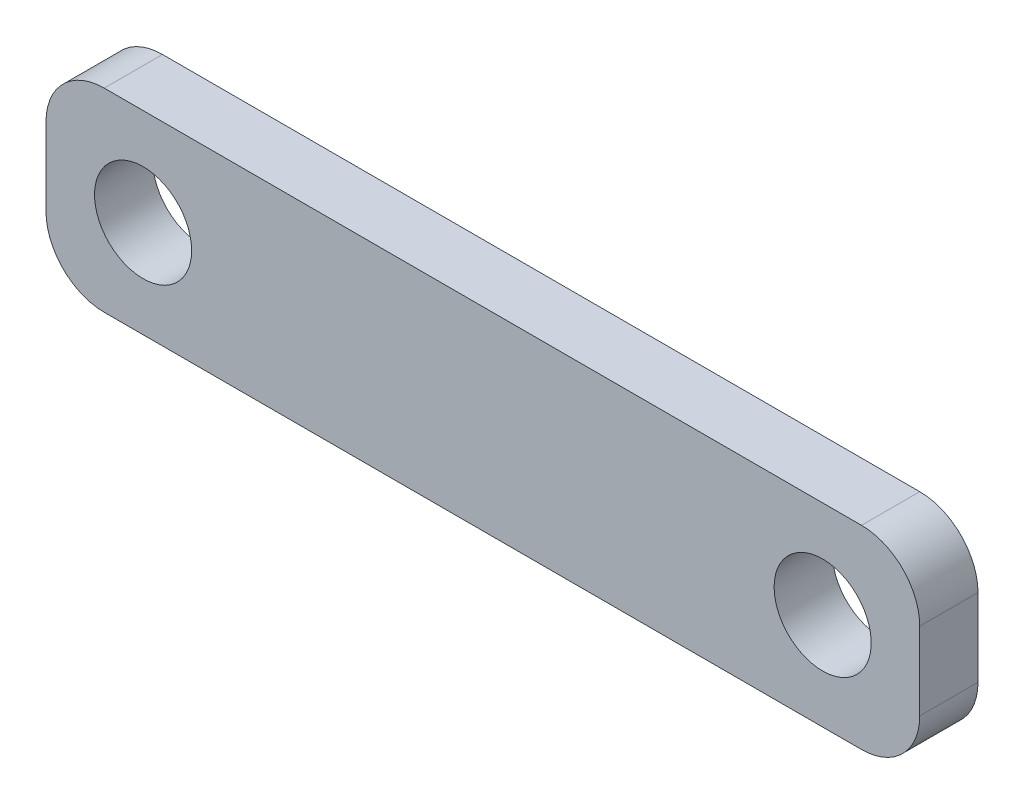
SolidWorks part; units mm, degrees
ref_plane "前视基准面" through (0, 0, 0) normal (0, 0, 1) x (1, 0, 0)
ref_plane "上视基准面" through (0, 0, 0) normal (0, 1, 0) x (1, 0, 0)
ref_plane "右视基准面" through (0, 0, 0) normal (1, 0, 0) x (0, 0, -1)
other "Configuration Table"
sketch "草图1" plane through (0, 0, 0) normal (0, 0, 1) x (1, 0, 0)
  line L0 (0, 5) -> (0, -5) construction
  line L1 (-19.5, -5) -> (19.5, -5)
  line L2 (-22.5, -2) -> (-22.5, 2)
  line L3 (-19.5, 5) -> (19.5, 5)
  line L4 (22.5, -2) -> (22.5, 2)
  line L5 (-22.5, -5) -> (22.5, 5) construction
  line L6 (-22.5, 5) -> (22.5, -5) construction
  arc A0 (19.5, -5) -> (22.5, -2) centre (19.5, -2) ccw
  arc A1 (-22.5, 2) -> (-19.5, 5) centre (-19.5, 2) cw
  arc A2 (-19.5, -5) -> (-22.5, -2) centre (-19.5, -2) cw
  arc A3 (19.5, 5) -> (22.5, 2) centre (19.5, 2) cw
  circle A4 centre (-17.5, 0) radius 2.5
  circle A5 centre (17.5, 0) radius 2.5
  point P0 (0, 0)
  dimension "D3" = 3
  dimension "D4" = 5
  dimension "D1" = 45
  dimension "D2" = 10
  dimension "D5" = 17.5
extrude "凸台-拉伸1" add sketch "草图1" along normal blind 3
